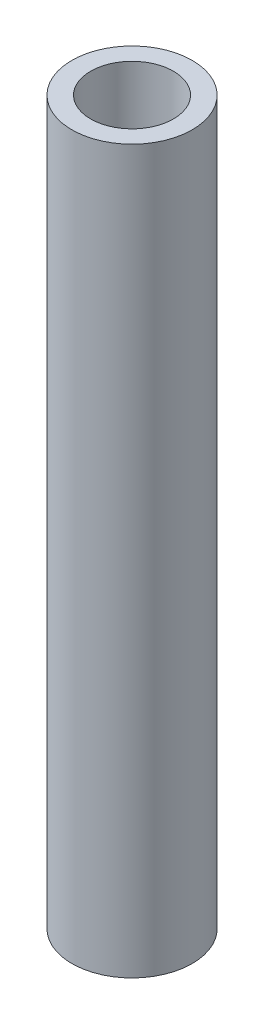
SolidWorks part; units mm, degrees
ref_plane "Front Plane" through (0, 0, 0) normal (0, 0, 1) x (1, 0, 0)
ref_plane "Top Plane" through (0, 0, 0) normal (0, 1, 0) x (1, 0, 0)
ref_plane "Right Plane" through (0, 0, 0) normal (1, 0, 0) x (0, 0, -1)
sketch "Sketch1" plane through (0, 0, 0) normal (0, 1, 0) x (1, 0, 0)
  circle A0 centre (0, 0) radius 1.5875
  dimension "D1" = 3.175
extrude "Boss-Extrude1" add sketch "Sketch1" along normal blind 19.05
hole_wizard "#2-56 Tapped Hole1" positions "Sketch3" profile "Sketch4" tap size "#2-56" standard "ANSI Inch" end condition through all
sketch "Sketch3" plane through (0, 19.05, 0) normal (0, 1, 0) x (1, 0, 0)
  point P0 (0, 0)
sketch "Sketch4" plane through (0, 19.05, 0) normal (1, 0, 0) x (0, 0, 1)
  line L0 (0, 0) -> (0, 19.05)
  line L1 (0, 19.05) -> (1.0922, 19.05)
  line L2 (1.0922, 19.05) -> (1.0922, 0)
  line L5 (1.0922, 0) -> (0, 0)
  line L11 (0, -6.35) -> (0, 107.95) construction
  dimension "Thread Major Dia." = 2.1844
  dimension "Thru Tap Drill Depth" = 19.05
